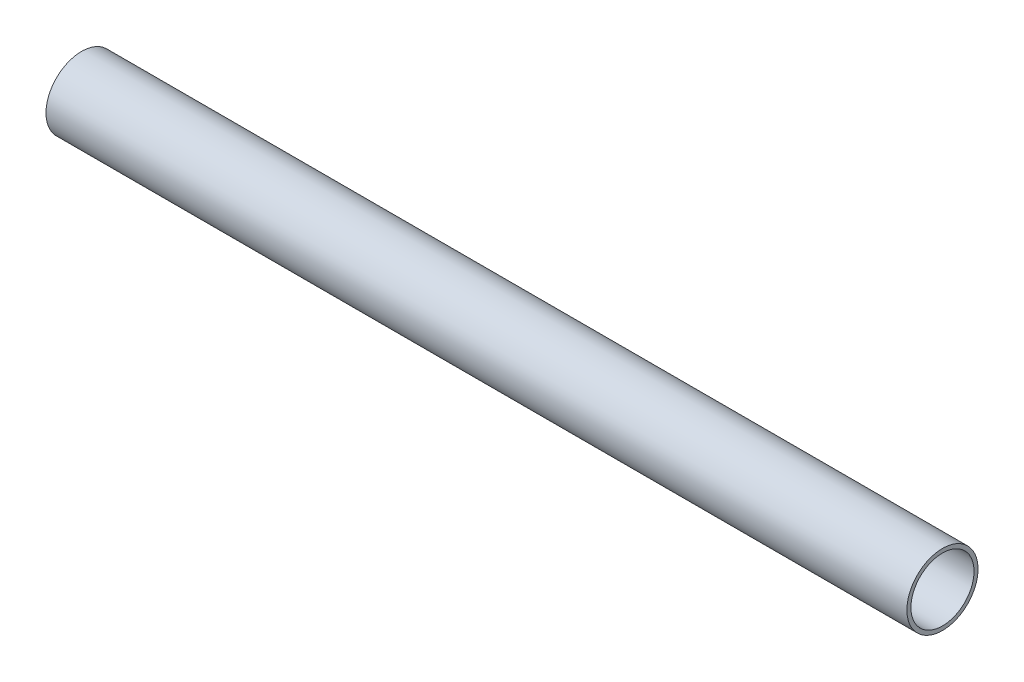
SolidWorks part; units mm, degrees
ref_plane "Front Plane" through (0, 0, 0) normal (0, 0, 1) x (1, 0, 0)
ref_plane "Top Plane" through (0, 0, 0) normal (0, 1, 0) x (1, 0, 0)
ref_plane "Right Plane" through (0, 0, 0) normal (1, 0, 0) x (0, 0, -1)
sketch "Sketch1" plane through (0, 0, 0) normal (1, 0, 0) x (0, 0, -1)
  circle A0 centre (0, 0) radius 1.5748
  circle A1 centre (0, 0) radius 1.397
extrude "Boss-Extrude1" add sketch "Sketch1" along normal blind 38.1
